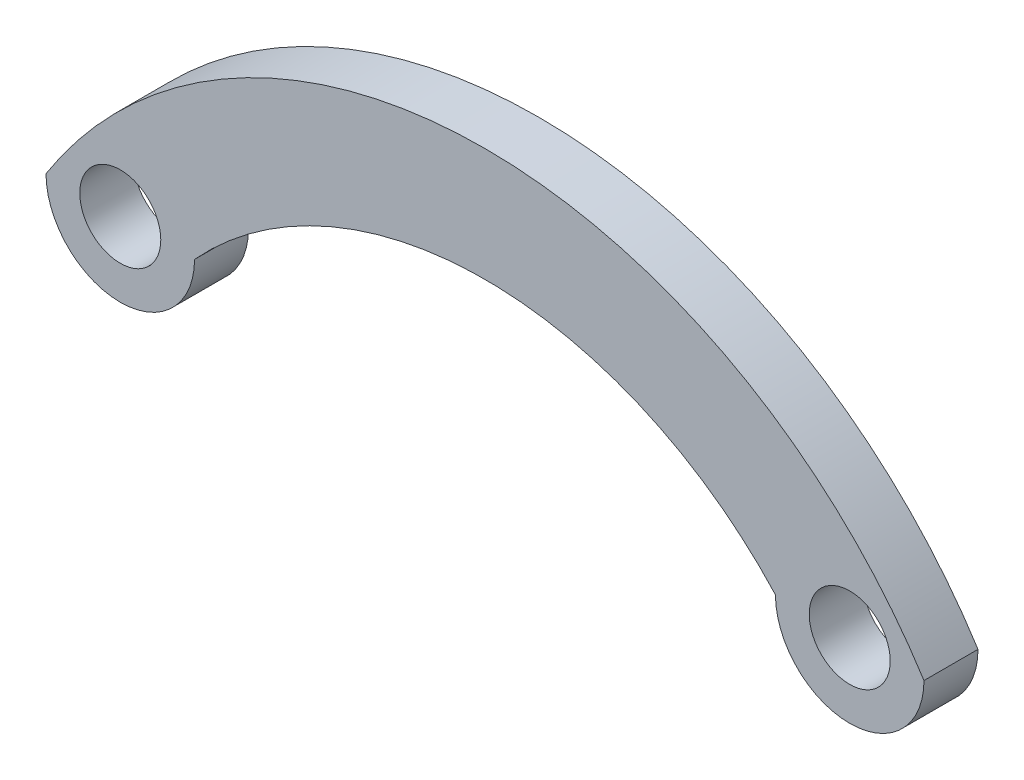
SolidWorks part; units mm, degrees
ref_plane "Alzado" through (0, 0, 0) normal (0, 0, 1) x (1, 0, 0)
ref_plane "Planta" through (0, 0, 0) normal (0, 1, 0) x (1, 0, 0)
ref_plane "Vista lateral" through (0, 0, 0) normal (1, 0, 0) x (0, 0, -1)
sketch "Croquis1" plane through (0, 0, 0) normal (0, 0, 1) x (1, 0, 0)
  line L0 (0, 0) -> (11, 0) construction
  line L1 (65.0169, 0) -> (54.0169, 0) construction
  arc A0 (0, 0) -> (65.0169, 0) centre (32.5085, -20.6435) cw
  arc A1 (11, 0) -> (54.0169, 0) centre (32.5085, -19.6845) cw
  arc A2 (0, 0) -> (11, 0) centre (5.5, 0) ccw
  arc A3 (54.0169, 0) -> (65.0169, 0) centre (59.5169, 0) ccw
  dimension "D1" = 11
  dimension "D2" = 11
extrude "Saliente-Extruir1" add sketch "Croquis1" along normal blind 4
sketch "Croquis3" plane through (0, 0, 4) normal (0, 0, 1) x (1, 0, 0)
  circle A0 centre (5.5, 0) radius 3
  circle A1 centre (59.5169, 0) radius 3
  dimension "D1" = 6
  dimension "D2" = 6
extrude "Cortar-Extruir2" cut sketch "Croquis3" against normal blind 4
